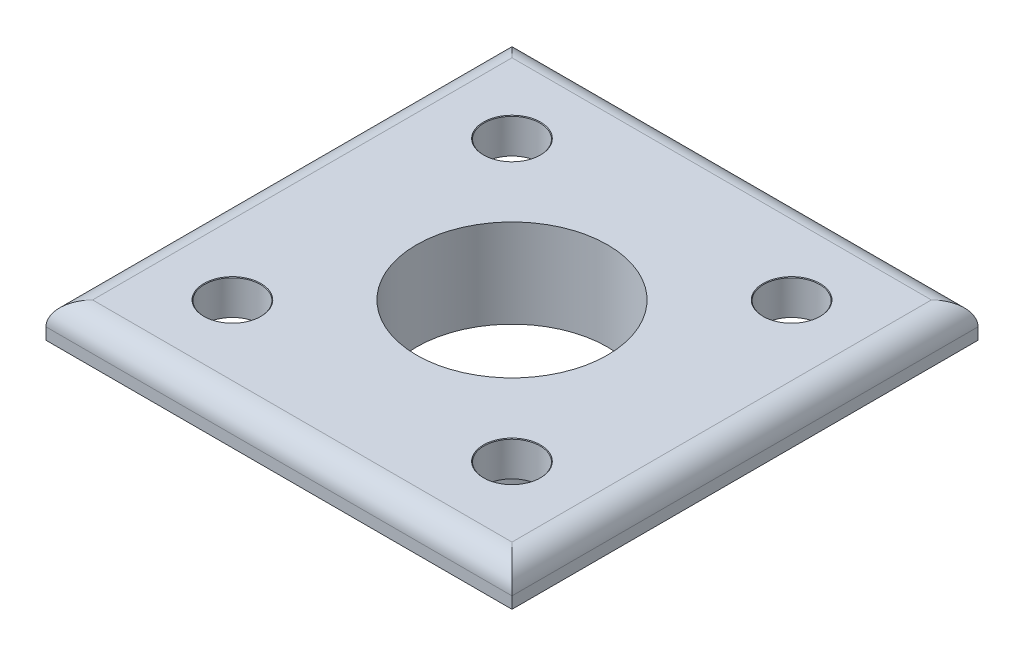
SolidWorks part; units mm, degrees
ref_plane "Front Plane" through (0, 0, 0) normal (0, 0, 1) x (1, 0, 0)
ref_plane "Top Plane" through (0, 0, 0) normal (0, 1, 0) x (1, 0, 0)
ref_plane "Right Plane" through (0, 0, 0) normal (1, 0, 0) x (0, 0, -1)
sketch "Sketch1" plane through (0, 0, 0) normal (0, 1, 0) x (1, 0, 0)
  line L5 (-10, -10) -> (10, -10)
  line L10 (-10, -10) -> (-10, 10)
  line L11 (-10, 10) -> (10, 10)
  line L12 (10, -10) -> (10, 10)
  line L13 (-10, -10) -> (10, 10) construction
  line L14 (-10, 10) -> (10, -10) construction
  dimension "D1" = 20
extrude "Boss-Extrude1" add sketch "Sketch1" along normal blind 1.5
sketch "Sketch2" plane through (0, 1.5, 0) normal (0, 1, 0) x (1, 0, 0)
  line L1 (-10, -10) -> (10, -10)
  line L2 (-10, -10) -> (-10, 10)
  line L3 (-10, 10) -> (10, 10)
  line L4 (10, -10) -> (10, 10)
  line L5 (-10, -10) -> (10, 10) construction
  line L6 (-10, 10) -> (10, -10) construction
  line L7 (-6, -6) -> (6, -6) construction
  line L8 (-6, -6) -> (-6, 6) construction
  line L9 (-6, 6) -> (6, 6) construction
  line L10 (6, -6) -> (6, 6) construction
  line L11 (-6, -6) -> (6, 6) construction
  line L12 (-6, 6) -> (6, -6) construction
  circle A0 centre (0, 0) radius 4.1
  point P0 (0, 0)
  point P7 (0, 0)
  dimension "D2" = 8.2
  dimension "D1" = 12
hole_wizard "M2 Clearance Hole1" positions "Sketch3" profile "Sketch5" hole size "M2" standard "ANSI Metric" end condition up to next
sketch "Sketch3" plane through (0, 1.5, 0) normal (0, 1, 0) x (1, 0, 0)
  point P0 (-6, 6)
  point P3 (6, 6)
  point P6 (-6, -6)
  point P9 (6, -6)
sketch "Sketch5" plane through (-6, 1.5, -6) normal (1, 0, 0) x (0, 0, 1)
  line L0 (0, 0) -> (0, 1.5)
  line L1 (0, 1.5) -> (1.2, 1.5)
  line L2 (1.2, 1.5) -> (1.2, 0.025)
  line L3 (1.2, 0.025) -> (1.225, 0)
  line L5 (1.225, 0) -> (0, 0)
  line L6 (-1.2, 0.025) -> (-1.225, 0) construction
  line L11 (0, -6.35) -> (0, 107.95) construction
  dimension "Thru Hole Dia." = 2.4
  dimension "Thru Hole Depth" = 1.5
  dimension "Near C'Sink Dia." = 2.45
  dimension "Near C'Sink Angle" = 90
fillet "Fillet1" radius 1 4 edges at (0, 1.5, 10) (10, 1.5, 0) (0, 1.5, -10) (-10, 1.5, 0)
extrude "Cut-Extrude1" cut sketch "Sketch2" against normal up to next contours A0
sketch "Sketch6" plane through (0, 0, 0) normal (0, -1, 0) x (1, 0, 0)
  circle A0 centre (0, 0) radius 4.1
  circle A1 centre (0, 0) radius 5.45
  circle A2 centre (0, 0) radius 4.1 construction
  circle M3 centre (0, 0) radius 4.1
  dimension "D1" = 10.9
extrude "Boss-Extrude2" add sketch "Sketch6" along normal blind 2.3 contours A1 M3 | A0
chamfer "Chamfer1" distance 0.5 angle 45 1 edges at (0, -2.3, -5.45)
